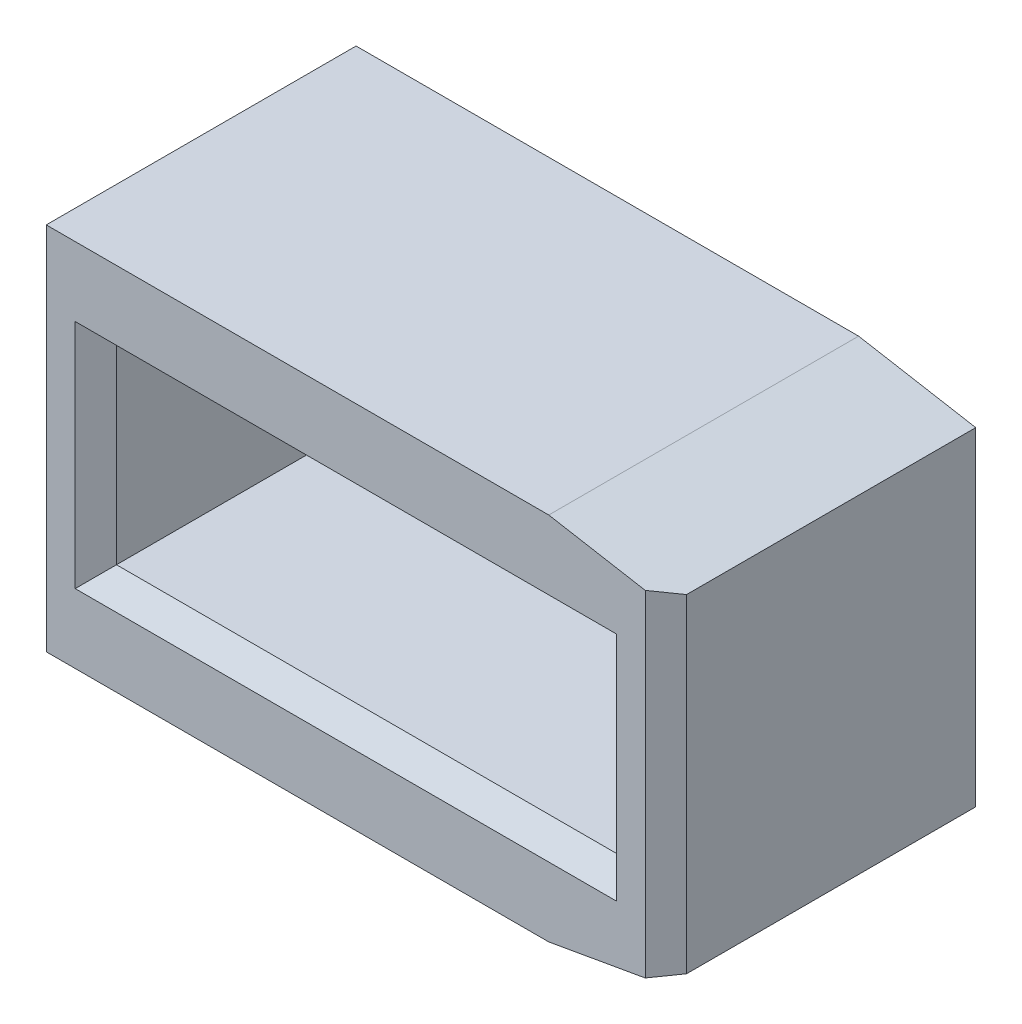
SolidWorks part; units mm, degrees
ref_plane "前视基准面" through (0, 0, 0) normal (0, 0, 1) x (1, 0, 0)
ref_plane "上视基准面" through (0, 0, 0) normal (0, 1, 0) x (1, 0, 0)
ref_plane "右视基准面" through (0, 0, 0) normal (1, 0, 0) x (0, 0, -1)
sketch "草图1" plane through (0, 0, 0) normal (0, 0, 1) x (1, 0, 0)
  line L1 (-30, 17.9) -> (30, 17.9)
  line L2 (-30, 17.9) -> (-30, -17.9)
  line L3 (-30, -17.9) -> (30, -17.9)
  line L4 (30, 17.9) -> (30, -17.9)
  line L5 (0, -17.9) -> (0, 17.9) construction
  line L6 (-30, 0) -> (30, 0) construction
  point P0 (0, 0)
  dimension "D1" = 60
  dimension "D2" = 35.8
extrude "凸台-拉伸1" add sketch "草图1" along normal blind 30
sketch "草图2" plane through (0, 0, 30) normal (0, 0, 1) x (1, 0, 0)
  line L1 (-25.2, -9.2) -> (25.2, -9.2)
  line L2 (-25.2, -9.2) -> (-25.2, 9.2)
  line L3 (-25.2, 9.2) -> (25.2, 9.2)
  line L4 (25.2, -9.2) -> (25.2, 9.2)
  line L5 (0, 9.2) -> (0, -9.2) construction
  line L6 (-25.2, 0) -> (25.2, 0) construction
  point P0 (0, 0)
  dimension "D1" = 50.4
  dimension "D2" = 18.4
extrude "切除-拉伸1" cut sketch "草图2" against normal through all
chamfer "倒角1" distance 2 angle 80 2 edges at (30, -17.9, 15) (30, 17.9, 15)
chamfer "倒角2" distance 2 4 edges at (0, -9.2, 30) (-25.2, 0, 30) (0, 9.2, 30) (30, 0, 30)
